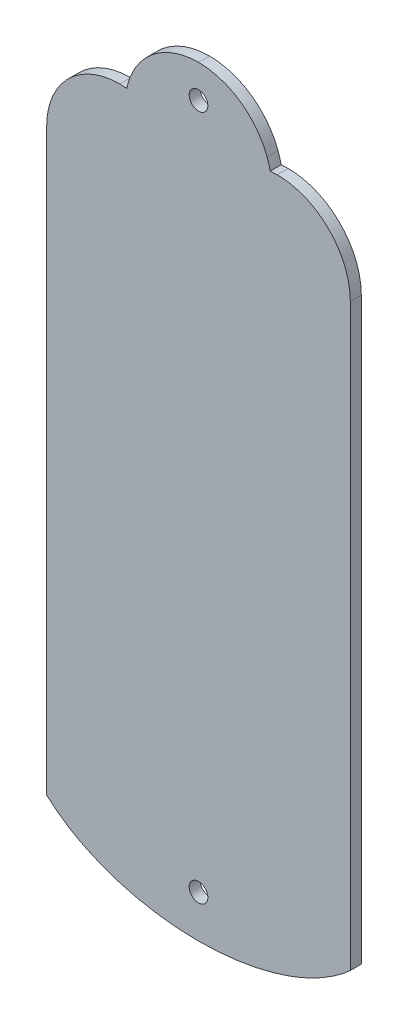
SolidWorks part; units mm, degrees
ref_plane "前视基准面" through (0, 0, 0) normal (0, 0, 1) x (1, 0, 0)
ref_plane "上视基准面" through (0, 0, 0) normal (0, 1, 0) x (1, 0, 0)
ref_plane "右视基准面" through (0, 0, 0) normal (1, 0, 0) x (0, 0, -1)
other "Configuration Table"
sketch "草图1" plane through (0, 0, 0) normal (0, 0, 1) x (1, 0, 0)
  line L4 (-41.5008, 68.1408) -> (-41.5008, -90.2458)
  line L5 (41.5008, 68.1408) -> (41.5008, -90.2458)
  circle A0 centre (0, 95) radius 2.55
  circle A1 centre (0, -92.4437) radius 2.55
  spline S0 degree 3 poles (41.5008, 68.1408) (41.5008, 79.1863) (32.5473, 88.1398) (21.5018, 88.1398) knots 0 0 0 0 1 1 1 1
  spline S1 degree 3 poles (21.5018, 88.1398) (20.8598, 88.1398) (20.2212, 88.108) (19.5933, 88.048) knots 1 1 1 1 2 2 2 2
  spline S2 degree 3 poles (19.5933, 88.048) (19.3887, 89.0464) (19.1064, 90.0201) (18.7607, 90.962) knots 2 2 2 2 3 3 3 3
  spline S3 degree 3 poles (18.7607, 90.962) (15.9385, 98.582) (8.6043, 104.0148) (0, 104.0148) knots 3 3 3 3 4 4 4 4
  spline S4 degree 3 poles (0, 104.0148) (-8.6043, 104.0148) (-15.9385, 98.582) (-18.7607, 90.962) knots 4 4 4 4 5 5 5 5
  spline S5 degree 3 poles (-18.7607, 90.962) (-19.1065, 90.0201) (-19.3887, 89.0464) (-19.5933, 88.048) knots 5 5 5 5 6 6 6 6
  spline S6 degree 3 poles (-19.5933, 88.048) (-20.2212, 88.108) (-20.8562, 88.1398) (-21.4983, 88.1398) knots 6 6 6 6 7 7 7 7
  spline S7 degree 3 poles (-21.4983, 88.1398) (-32.5473, 88.1398) (-41.5008, 79.1863) (-41.5008, 68.1408) knots 7 7 7 7 8 8 8 8
  spline S9 degree 3 poles (-41.5008, -90.2458) (-38.3893, -93.0892) (-34.5687, -95.594) (-30.1978, -97.6648) knots 11 11 11 11 12 12 12 12
  spline S10 degree 3 poles (-30.1978, -97.6648) (-21.7805, -101.6547) (-11.3242, -104.0148) (0, -104.0148) knots 12 12 12 12 13 13 13 13
  spline S11 degree 3 poles (0, -104.0148) (11.3242, -104.0148) (21.7805, -101.6547) (30.1978, -97.6648) knots 13 13 13 13 14 14 14 14
  spline S12 degree 3 poles (30.1978, -97.6648) (34.5687, -95.594) (38.3893, -93.0892) (41.5008, -90.2458) knots 14 14 14 14 15 15 15 15
extrude "凸台-拉伸1" add sketch "草图1" along normal blind 3
equation "\"、\"=3"
